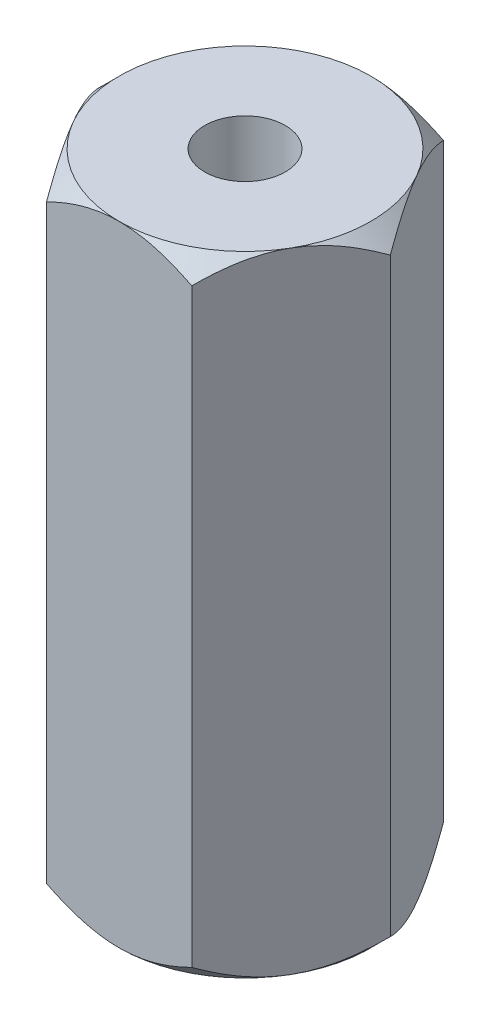
SolidWorks part; units mm, degrees
ref_plane "Front Plane" through (0, 0, 0) normal (0, 0, 1) x (1, 0, 0)
ref_plane "Top Plane" through (0, 0, 0) normal (0, 1, 0) x (1, 0, 0)
ref_plane "Right Plane" through (0, 0, 0) normal (1, 0, 0) x (0, 0, -1)
sketch "Sketch1" plane through (0, 0, 0) normal (0, 1, 0) x (1, 0, 0)
  line L1 (3.695, 0) -> (1.8475, 3.2)
  line L2 (1.8475, 3.2) -> (-1.8475, 3.2)
  line L3 (-1.8475, 3.2) -> (-3.695, 0)
  line L4 (-3.695, 0) -> (-1.8475, -3.2)
  line L5 (-1.8475, -3.2) -> (1.8475, -3.2)
  line L6 (1.8475, -3.2) -> (3.695, 0)
  circle A0 centre (0, 0) radius 3.2 construction
  dimension "D1" = 6.4
extrude "Boss-Extrude1" add sketch "Sketch1" along normal mid plane 16
sketch "Sketch3" plane through (0, 8, 0) normal (0, 1, 0) x (1, 0, 0)
  circle A0 centre (0, 0) radius 3.2
extrude "Cut-Extrude1" cut sketch "Sketch3" against normal blind 10 draft 45 flip side to cut
mirror "Mirror2" about plane through (0, 0, 0) normal (0, 1, 0) of "Cut-Extrude1"
hole_wizard "M2.5 Tapped Hole1" positions "3DSketch1" profile "Sketch2" tap size "M2.5" standard "ISO"
sketch3d "3DSketch1"
  point P0 (0, 8, 0)
sketch "Sketch2" plane through (0, 8, 0) normal (1, 0, 0) x (0, 0, 1)
  line L0 (0, 0) -> (0, 6.9659)
  line L1 (0, 6.9659) -> (1.025, 6.35)
  line L2 (1.025, 6.35) -> (1.025, 0)
  line L5 (1.025, 0) -> (0, 0)
  line L10 (0, 6.9659) -> (-1.025, 6.35) construction
  line L11 (0, -6.35) -> (0, 107.95) construction
  dimension "Tap Drill Dia." = 2.05
  dimension "Tap Drill Depth" = 6.35
  dimension "Drill Angle" = 118
cosmetic thread "Hole Thread1" parameters "D1"=5, "D2"=2.5
mirror "Mirror1" about plane through (0, 0, 0) normal (0, 1, 0) of "M2.5 Tapped Hole1"
